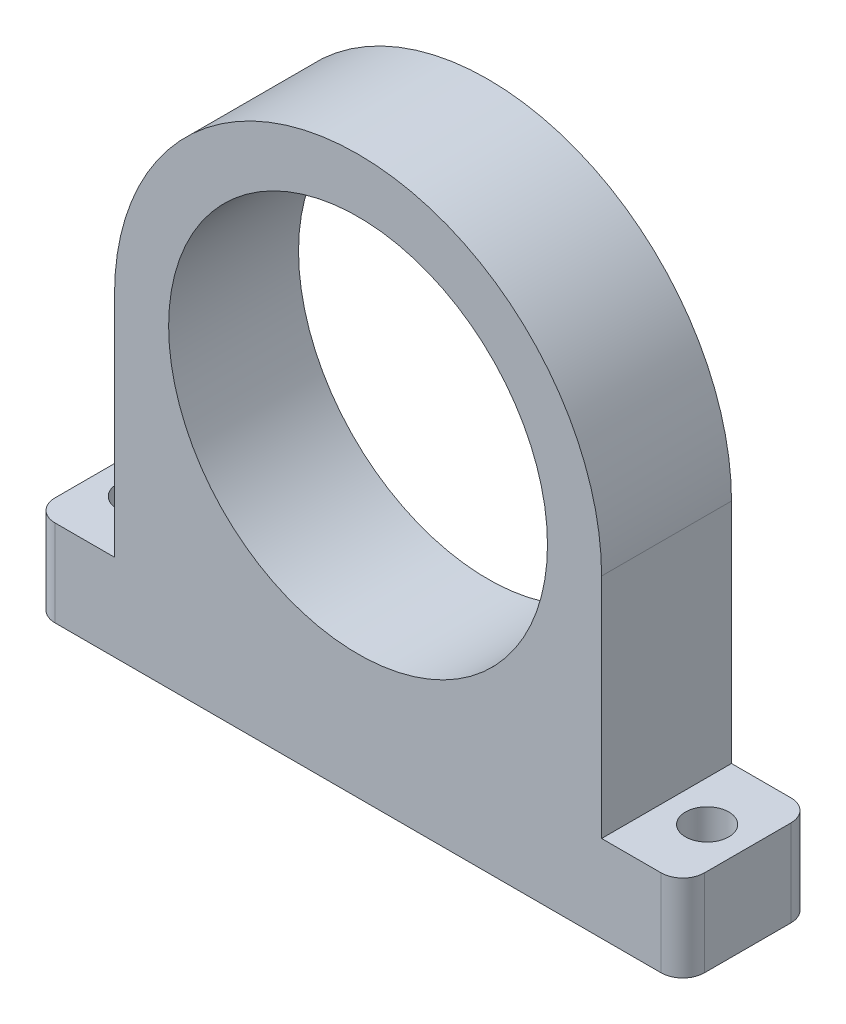
SolidWorks part; units mm, degrees
ref_plane "Alzado" through (0, 0, 0) normal (0, 0, 1) x (1, 0, 0)
ref_plane "Planta" through (0, 0, 0) normal (0, 1, 0) x (1, 0, 0)
ref_plane "Vista lateral" through (0, 0, 0) normal (1, 0, 0) x (0, 0, -1)
sketch "Croquis1" plane through (0, 0, 0) normal (0, 0, 1) x (1, 0, 0)
  line L0 (30, 0) -> (-30, 0)
  line L1 (0, 29) -> (0, 0) construction
  line L2 (-30, 0) -> (-30, 8)
  line L3 (-30, 8) -> (-22.5, 8)
  line L4 (-22.5, 29) -> (-22.5, 8)
  line L5 (30, 0) -> (30, 8)
  line L6 (30, 8) -> (22.5, 8)
  line L7 (22.5, 29) -> (22.5, 8)
  arc A0 (22.5, 29) -> (-22.5, 29) centre (0, 29) ccw
  circle A1 centre (0, 29) radius 17.5
  point P12 (0, 11.5)
  dimension "D1" = 35
  dimension "D2" = 5
  dimension "D4" = 11.5
  dimension "D3" = 8
  dimension "D5" = 60
extrude "Saliente-Extruir1" add sketch "Croquis1" along normal mid plane 12
sketch "Croquis2" plane through (0, 8, 0) normal (0, 1, 0) x (1, 0, 0)
  line L0 (-26.25, 6) -> (-26.25, -6) construction
  line L3 (-30, 0) -> (-22.5, 0) construction
  line L4 (-30, -6) -> (-30, 6) construction
  line L5 (-22.5, -6) -> (-22.5, 6) construction
  line L6 (-22.5, 6) -> (-30, 6) construction
  line L7 (-22.5, -6) -> (-30, -6) construction
  line L8 (0, 6) -> (0, -6) construction
  line L9 (22.5, 6) -> (-22.5, 6) construction
  line L10 (-22.5, -6) -> (22.5, -6) construction
  circle A0 centre (-26.25, 0) radius 2
  circle A1 centre (26.25, 0) radius 2
extrude "Cortar-Extruir1" cut sketch "Croquis2" against normal through all
fillet "Redondeo1" radius 2 4 edges at (30, 4, -6) (-30, 4, -6) (-30, 4, 6) (30, 4, 6)
